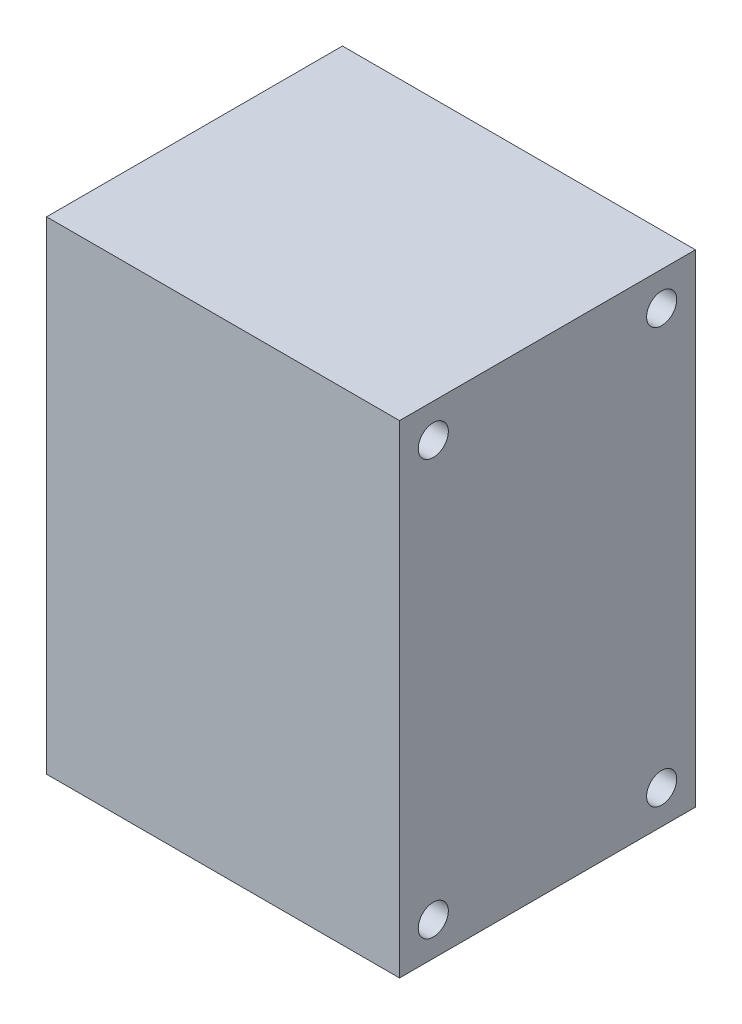
SolidWorks part; units mm, degrees
ref_plane "Front Plane" through (0, 0, 0) normal (0, 0, 1) x (1, 0, 0)
ref_plane "Top Plane" through (0, 0, 0) normal (0, 1, 0) x (1, 0, 0)
ref_plane "Right Plane" through (0, 0, 0) normal (1, 0, 0) x (0, 0, -1)
sketch "Sketch1" plane through (0, 0, 0) normal (0, 0, 1) x (1, 0, 0)
  line L1 (-17, 23.25) -> (17, 23.25)
  line L2 (-17, 23.25) -> (-17, -23.25)
  line L3 (-17, -23.25) -> (17, -23.25)
  line L4 (17, 23.25) -> (17, -23.25)
  line L5 (-17, 23.25) -> (17, -23.25) construction
  line L6 (-17, -23.25) -> (17, 23.25) construction
  point P0 (0, 0)
  dimension "D1" = 34
  dimension "D2" = 46.5
extrude "Boss-Extrude1" add sketch "Sketch1" along normal blind 28.5
sketch "Sketch2" plane through (17, 0, 0) normal (1, 0, 0) x (0, 0, -1)
  line L0 (-28.5, -23.25) -> (-28.5, 23.25) construction
  line L1 (-28.5, 23.25) -> (0, 23.25) construction
  circle A0 centre (-25.25, 20) radius 1.45
  circle A1 centre (-3.25, 20) radius 1.45
  circle A2 centre (-3.25, -20) radius 1.45
  circle A3 centre (-25.25, -20) radius 1.45
  dimension "D1" = 2.9
  dimension "D2" = 3.25
  dimension "D3" = 3.25
  dimension "D4" = 2
  dimension "D5" = 2
extrude "Cut-Extrude1" cut sketch "Sketch2" against normal through all
